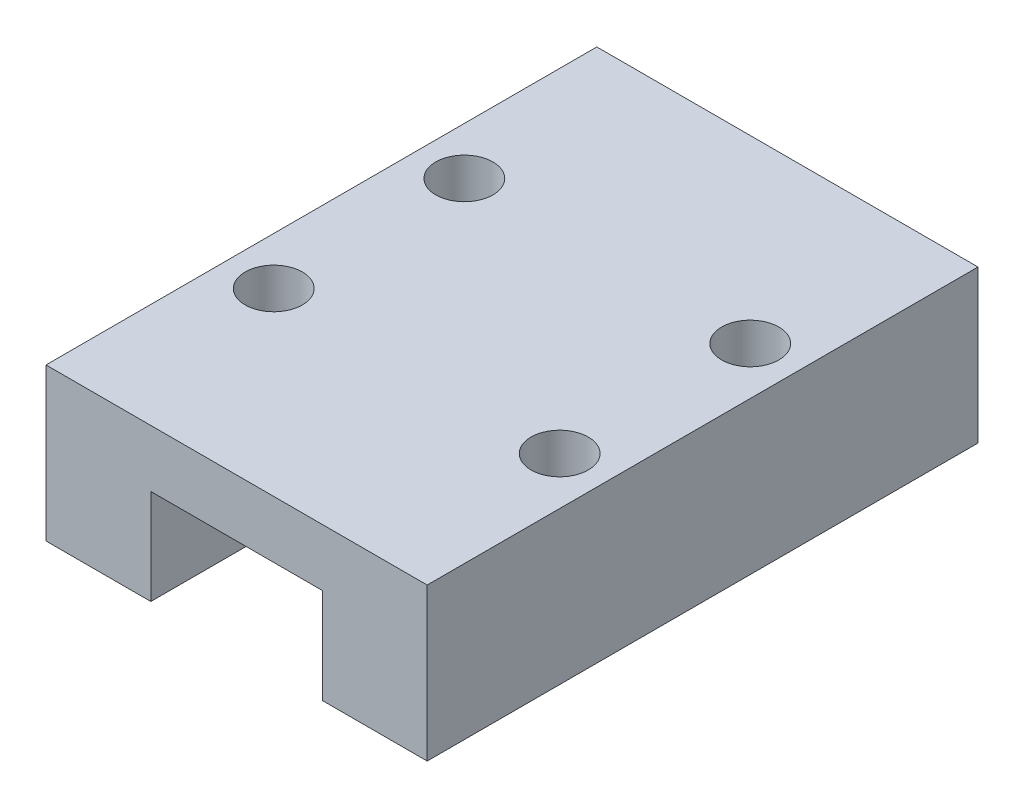
SolidWorks part; units mm, degrees
material "自定义塑料"
ref_plane "前视基准面" through (0, 0, 0) normal (0, 0, 1) x (1, 0, 0)
ref_plane "上视基准面" through (0, 0, 0) normal (0, 1, 0) x (1, 0, 0)
ref_plane "右视基准面" through (0, 0, 0) normal (1, 0, 0) x (0, 0, -1)
sketch "草图1" plane through (0, 0, 0) normal (0, 0, 1) x (1, 0, 0)
  line L0 (-10, 8) -> (-10, -5.2045) construction
  line L1 (0, 0) -> (-5.5, 0)
  line L2 (0, 0) -> (0, 8)
  line L3 (0, 8) -> (-20, 8)
  line L4 (-20, 0) -> (-20, 8)
  line L5 (-14.5, 0) -> (-14.5, 5)
  line L6 (-14.5, 5) -> (-5.5, 5)
  line L7 (-5.5, 0) -> (-5.5, 5)
  line L8 (-14.5, 0) -> (-20, 0)
  point P12 (-10, 5)
  dimension "D1" = 20
  dimension "D2" = 8
  dimension "D3" = 9
  dimension "D4" = 5
extrude "凸台-拉伸1" add sketch "草图1" along normal blind 28.9
sketch "草图2" plane through (0, 8, 0) normal (0, 1, 0) x (1, 0, 0)
  line L0 (-10, 0) -> (-10, -50000) construction
  line L1 (0, 0) -> (-20, 0) construction
  line L2 (0, -28.9) -> (-20, -28.9) construction
  line L3 (-20, -14.45) -> (49980, -14.45) construction
  line L4 (-20, -28.9) -> (-20, 0) construction
  line L5 (0, -28.9) -> (0, 0) construction
  circle A0 centre (-17.5, -9.45) radius 1.5
  circle A1 centre (-2.5, -9.45) radius 1.5
  circle A2 centre (-2.5, -19.45) radius 1.5
  circle A3 centre (-17.5, -19.45) radius 1.5
  point P4 (-10, 0)
  point P7 (-10, -28.9)
  point P16 (-20, -14.45)
  point P19 (0, -14.45)
  dimension "D3" = 3
  dimension "D1" = 15
  dimension "D2" = 10
extrude "切除-拉伸1" cut sketch "草图2" against normal blind 5
